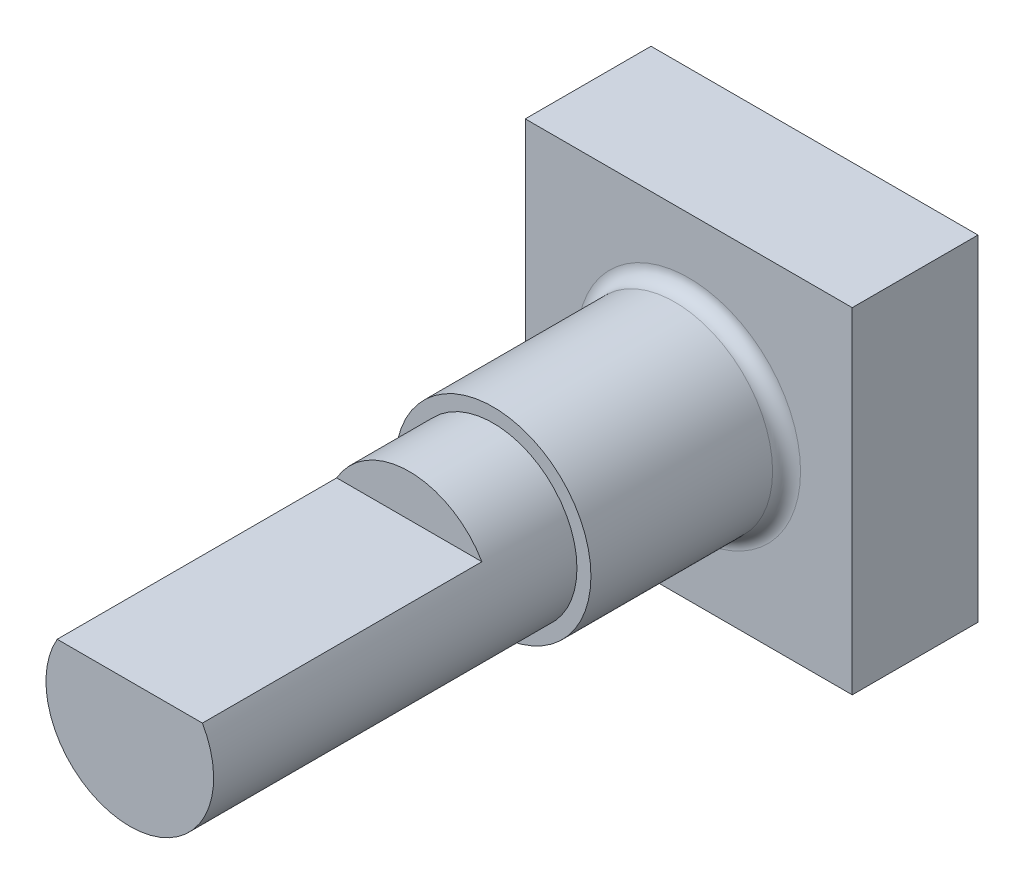
SolidWorks part; units mm, degrees
ref_plane "前视基准面" through (0, 0, 0) normal (0, 0, 1) x (1, 0, 0)
ref_plane "上视基准面" through (0, 0, 0) normal (0, 1, 0) x (1, 0, 0)
ref_plane "右视基准面" through (0, 0, 0) normal (1, 0, 0) x (0, 0, -1)
other "Configuration Table"
sketch "草图1" plane through (0, 0, 0) normal (0, 0, 1) x (1, 0, 0)
  line L1 (0, 0) -> (11.7, 0)
  line L2 (0, 0) -> (0, 12)
  line L3 (0, 12) -> (11.7, 12)
  line L4 (11.7, 0) -> (11.7, 12)
  dimension "D1" = 11.7
  dimension "D2" = 12
extrude "凸台-拉伸1" add sketch "草图1" along normal blind 4.5
sketch "草图2" plane through (0, 0, 4.5) normal (0, 0, 1) x (1, 0, 0)
  line L0 (5.85, 12) -> (5.85, -0.5329) construction
  line L1 (11.7, 12) -> (0, 12) construction
  line L2 (0, 6) -> (13.0109, 6) construction
  line L3 (0, 12) -> (0, 0) construction
  circle A0 centre (5.85, 6) radius 3.5
  point P10 (0, 0)
  point P11 (0, 0)
  dimension "D1" = 7
extrude "凸台-拉伸2" add sketch "草图2" along normal blind 7
sketch "草图3" plane through (0, 0, 11.5) normal (0, 0, 1) x (1, 0, 0)
  circle A0 centre (5.85, 6) radius 3
  dimension "D1" = 6
extrude "凸台-拉伸3" add sketch "草图3" along normal blind 13
sketch "草图4" plane through (0, 0, 24.5) normal (0, 0, 1) x (1, 0, 0)
  line L0 (3.2519, 7.5) -> (8.4481, 7.5)
  circle A0 centre (5.85, 6) radius 3 construction
  arc A2 (8.4481, 7.5) -> (3.2519, 7.5) centre (5.85, 6) ccw
  dimension "D1" = 1.5
extrude "切除-拉伸1" cut sketch "草图4" against normal blind 10
fillet "圆角1" radius 0.5 1 edges at (9.35, 6, 4.5)
